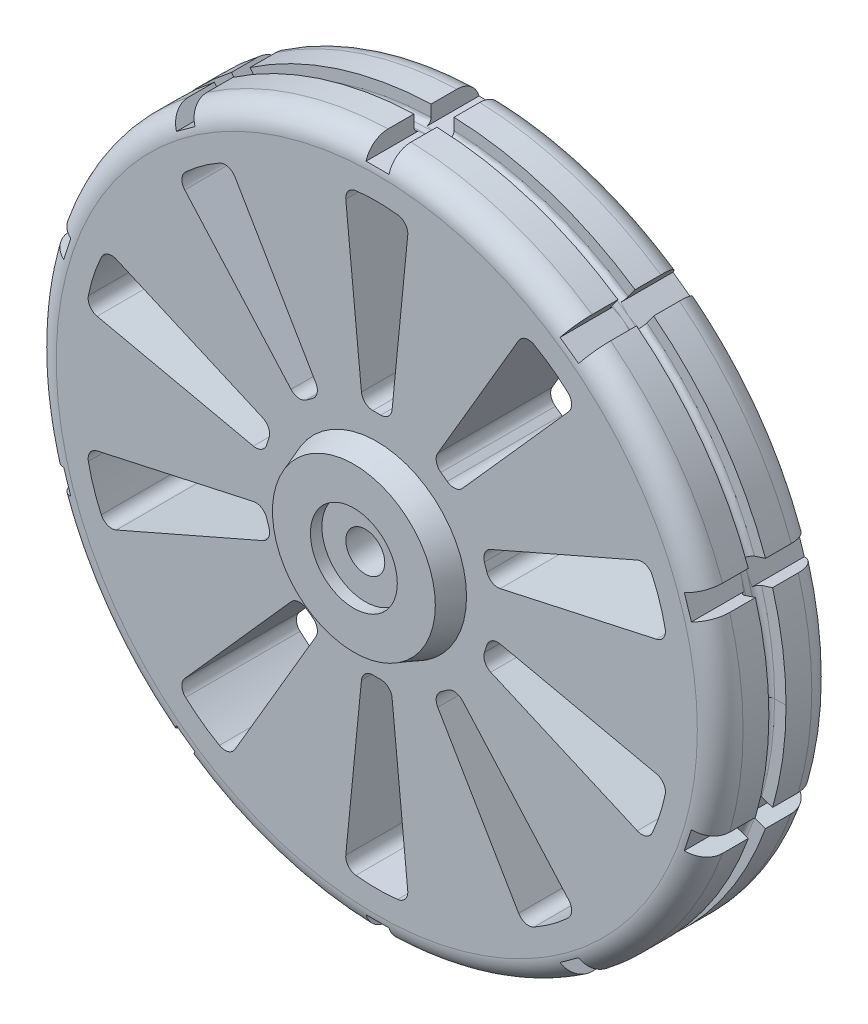
SolidWorks part; units mm, degrees
ref_plane "Front Plane" through (0, 0, 0) normal (0, 0, 1) x (1, 0, 0)
ref_plane "Top Plane" through (0, 0, 0) normal (0, 1, 0) x (1, 0, 0)
ref_plane "Right Plane" through (0, 0, 0) normal (1, 0, 0) x (0, 0, -1)
sketch "Sketch1" plane through (0, 0, 0) normal (0, 0, 1) x (1, 0, 0)
  circle A0 centre (0, 0) radius 30
  dimension "D1" = 60
extrude "Boss-Extrude1" add sketch "Sketch1" against normal blind 10
sketch "Sketch3" plane through (0, 0, 0) normal (0, 0, 1) x (1, 0, 0)
  circle A0 centre (0, 0) radius 1
  dimension "D1" = 2
extrude "Cut-Extrude1" cut sketch "Sketch3" against normal through all
sketch "Sketch4" plane through (0, 0, 0) normal (0, 0, 1) x (1, 0, 0)
  line L0 (-1.6802, 2.3637) -> (-2.6877, -1.0892)
  line L1 (1.6802, -2.3637) -> (2.6877, 1.0892)
  line L2 (-1.3368, 2.1126) -> (-2.2631, -1.0622)
  line L3 (1.3368, -2.1126) -> (2.2631, 1.0622)
  line L4 (-1.3368, 2.1126) -> (-2.2631, -1.0622) construction
  line L5 (1.3368, -2.1126) -> (2.2631, 1.0622) construction
  arc A0 (-2.6877, -1.0892) -> (1.6802, -2.3637) centre (0, 0) ccw
  arc A1 (2.6877, 1.0892) -> (-1.6802, 2.3637) centre (0, 0) ccw
  arc A2 (-2.2631, -1.0622) -> (1.3368, -2.1126) centre (0, 0) ccw
  arc A3 (2.2631, 1.0622) -> (-1.3368, 2.1126) centre (0, 0) ccw
  arc A4 (-2.2631, -1.0622) -> (1.3368, -2.1126) centre (0, 0) ccw construction
  arc A5 (2.2631, 1.0622) -> (-1.3368, 2.1126) centre (0, 0) ccw construction
  dimension "D1" = 0
  dimension "D2" = 0.4
extrude "Cut-Extrude2" cut sketch "Sketch4" against normal through all
sketch "Sketch12" plane through (0, 0, 0) normal (0, 0, 1) x (1, 0, 0)
  circle A0 centre (0, 0) radius 5
  dimension "D1" = 10
extrude "Boss-Extrude3" add sketch "Sketch12" against normal offset from surface (4 mm away) 6 up to face at (0, 0, -10)
sketch "Sketch5" plane through (0, 0, 0) normal (0, 0, 1) x (1, 0, 0)
  circle A0 centre (0, 0) radius 7.8416
extrude "Boss-Extrude2" add sketch "Sketch5" along normal blind 2 draft 20
sketch "Sketch6" plane through (0, 0, 2) normal (0, 0, 1) x (1, 0, 0)
  circle A0 centre (0, 0) radius 1.7
  dimension "D1" = 3.4
extrude "Cut-Extrude3" cut sketch "Sketch6" against normal through all contours A0
sketch "Sketch7" plane through (0, 0, 0) normal (0, 0, 1) x (1, 0, 0)
  line L0 (0, 0) -> (0, 30) construction
  line L1 (-2.8, 25.7531) -> (-1.25, 10)
  line L2 (2.8, 25.7531) -> (1.25, 10)
  line L3 (1.25, 10) -> (-1.25, 10)
  circle A0 centre (0, 0) radius 30 construction
  arc A2 (0, 26) -> (-2.8, 25.7531) centre (0, 10) ccw
  arc A3 (0, 26) -> (2.8, 25.7531) centre (0, 10) cw
  point P12 (0, 10)
  dimension "D2" = 2.8
  dimension "D1" = 2.8
  dimension "D3" = 2.5
  dimension "D4" = 20
  dimension "D5" = 4
extrude "Cut-Extrude4" cut sketch "Sketch7" against normal through all
pattern_circular "CirPattern1" count 10 over 360 about axis through (0, 0, 0) along (0, 0, 1) of "Cut-Extrude4"
fillet "Fillet1" radius 1 40 edges at (9.8968, 1.9013, -5) (9.1243, 4.279, -5) (23.6274, 10.6211, -5) (25.3579, 5.2952, -5) (6.8891, 7.3554, -5) (4.8666, 8.8249, -5) (12.872, 22.4805, -5) (17.4025, 19.1889, -5) (4.8666, -8.8249, -5) (6.8891, -7.3554, -5) (17.4025, -19.1889, -5) (12.872, -22.4805, -5) (9.1243, -4.279, -5) (9.8968, -1.9013, -5) (25.3579, -5.2952, -5) (23.6274, -10.6211, -5) (-9.1243, 4.279, -5) (-9.8968, 1.9013, -5) (-25.3579, 5.2952, -5) (-23.6274, 10.6211, -5) (-9.8968, -1.9013, -5) (-9.1243, -4.279, -5) (-23.6274, -10.6211, -5) (-25.3579, -5.2952, -5) (-6.8891, -7.3554, -5) (-4.8666, -8.8249, -5) (-12.872, -22.4805, -5) (-17.4025, -19.1889, -5) (-1.25, -10, -5) (1.25, -10, -5) (2.8, -25.7531, -5) (-2.8, -25.7531, -5) (-4.8666, 8.8249, -5) (-6.8891, 7.3554, -5) (-17.4025, 19.1889, -5) (-12.872, 22.4805, -5) (1.25, 10, -5) (-1.25, 10, -5) (-2.8, 25.7531, -5) (2.8, 25.7531, -5)
fillet "Fillet2" radius 2 2 edges at (30, 0, -10) (30, 0, 0)
sketch "Sketch8" plane through (0, 0, 0) normal (1, 0, 0) x (0, 0, -1)
  line L0 (4.25, 30) -> (4.25, 28.5)
  line L1 (8, 30) -> (2, 30) construction
  line L2 (4.25, 28.5) -> (5.75, 28.5)
  line L3 (5.75, 28.5) -> (5.75, 30)
  line L4 (5.75, 30) -> (4.25, 30)
  line L5 (8, 30) -> (2, 30) construction
  point P6 (5, 30)
  point P7 (5, 30)
  dimension "D1" = 1.5
  dimension "D2" = 1.5
sweep "Cut-Sweep1" cut profiles "Sketch8" path edge at (28, 0, 0)
fillet "Fillet3" radius 0.5 4 edges at (-20.1525, -20.1525, -5.75) (20.1525, 20.1525, -5.75) (-20.1525, -20.1525, -4.25) (20.1525, 20.1525, -4.25)
sketch "Sketch11" plane through (0, 0, 0) normal (0, 0, 1) x (1, 0, 0)
  line L0 (0, 30) -> (0, 0) construction
  line L1 (-1, 28.5) -> (1, 28.5)
  line L2 (-1, 28.5) -> (-1, 31.5)
  line L3 (-1, 31.5) -> (1, 31.5)
  line L4 (1, 28.5) -> (1, 31.5)
  line L5 (-1, 28.5) -> (1, 31.5) construction
  line L6 (-1, 31.5) -> (1, 28.5) construction
  circle A0 centre (0, 0) radius 30 construction
  point P0 (0, 30)
  dimension "D1" = 2
  dimension "D2" = 3
extrude "Cut-Extrude5" cut sketch "Sketch11" against normal through all
pattern_circular "CirPattern2" count 10 over 360 about axis through (0, 0, 0) along (0, 0, 1) of "Cut-Extrude5"
sketch "Sketch13" plane through (0, 0, 2) normal (0, 0, 1) x (1, 0, 0)
  circle A0 centre (0, 0) radius 3.7936
extrude "Cut-Extrude6" cut sketch "Sketch13" against normal blind 1
